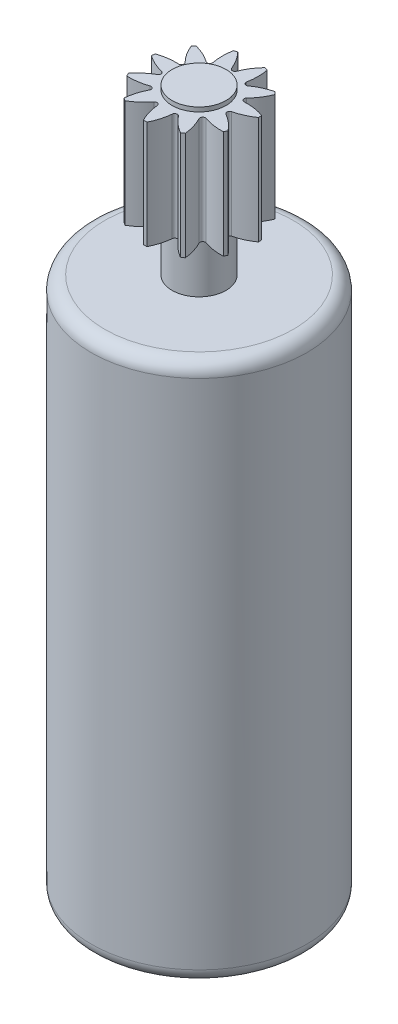
SolidWorks part; units mm, degrees
ref_plane "Ön Düzlem" through (0, 0, 0) normal (0, 0, 1) x (1, 0, 0)
ref_plane "Üst Düzlem" through (0, 0, 0) normal (0, 1, 0) x (1, 0, 0)
ref_plane "Sağ Düzlem" through (0, 0, 0) normal (1, 0, 0) x (0, 0, -1)
sketch "Çizim1" plane through (0, 0, 0) normal (0, 0, 1) x (1, 0, 0)
  line L0 (0, 0) -> (0, 26.1)
  line L1 (0, 26.1) -> (1, 26.1)
  line L2 (1, 26.1) -> (1, 25.9393)
  line L3 (1, 25.9393) -> (2, 25.9393)
  line L4 (2, 25.9393) -> (2, 21.9393)
  line L5 (2, 21.9393) -> (1, 21.9393)
  line L6 (1, 21.9393) -> (1, 20)
  line L7 (1, 20) -> (4, 20)
  line L8 (4, 20) -> (4, 0)
  line L9 (4, 0) -> (0, 0)
  dimension "D1" = 26.1
  dimension "D2" = 4
  dimension "D3" = 20
  dimension "D4" = 3
  dimension "D5" = 4
  dimension "D6" = 1
  dimension "D7" = 1
revolve "Döndür1" add sketch "Çizim1" angle 360 about L0
fillet "Radyus1" radius 0.5 2 edges at (0, 0, -4) (0, 20, -4)
sketch "Çizim2" plane through (0, 25.9393, 0) normal (0, 1, 0) x (1, 0, 0)
  line L0 (0, 0) -> (0, 4.4475) construction
  circle A0 centre (0, 0) radius 2 construction
  arc A1 (0.5, 1.9365) -> (-0.5, 1.9365) centre (0, 0) ccw
  arc A2 (-0.5, 1.9365) -> (-0.093, 1.2986) centre (-1.952, 0.5611) cw
  arc A3 (0.093, 1.2986) -> (0.5, 1.9365) centre (1.952, 0.5611) cw
  arc A4 (-0.093, 1.2986) -> (0.093, 1.2986) centre (0, 1.3354) ccw
  point P12 (0, 0.9965)
  dimension "D1" = 2
  dimension "D2" = 2
  dimension "D4" = 0.1
  dimension "D3" = 1
extrude "Kes-Ekstrüzyon1" cut sketch "Çizim2" against normal blind 4
pattern_circular "Dairesel Kaplama1" count 11 over 360 about axis through (0, 0, 0) along (0, 1, 0) of "Kes-Ekstrüzyon1"
